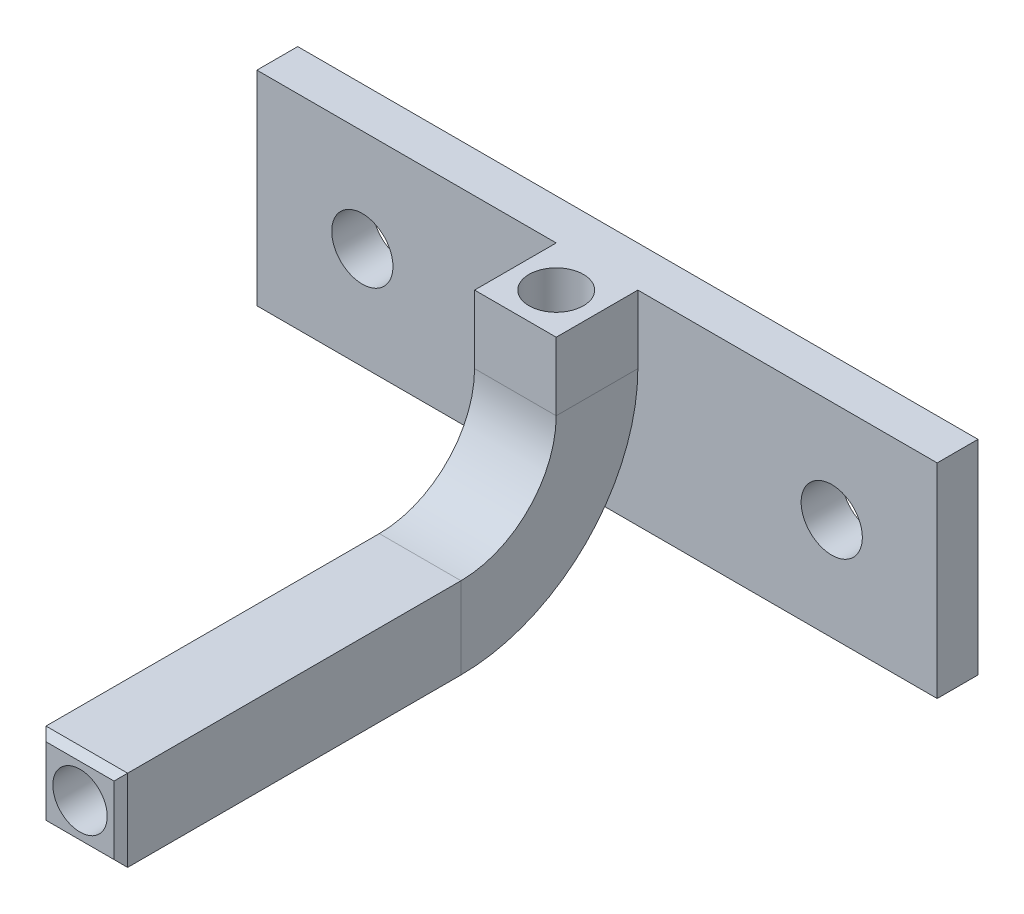
SolidWorks part; units mm, degrees
ref_plane "Спереди" through (0, 0, 0) normal (0, 0, 1) x (1, 0, 0)
ref_plane "Сверху" through (0, 0, 0) normal (0, 1, 0) x (1, 0, 0)
ref_plane "Справа" through (0, 0, 0) normal (1, 0, 0) x (0, 0, -1)
sketch "Эскиз1" plane through (0, 0, 0) normal (0, 0, 1) x (1, 0, 0)
  line L0 (-17.25, 0) -> (17.25, 0) construction
  line L1 (-25, -7.5) -> (25, -7.5)
  line L2 (-25, -7.5) -> (-25, 7.5)
  line L3 (-25, 7.5) -> (25, 7.5)
  line L4 (25, -7.5) -> (25, 7.5)
  line L5 (-25, -7.5) -> (25, 7.5) construction
  line L6 (-25, 7.5) -> (25, -7.5) construction
  circle A0 centre (17.25, 0) radius 2.25
  circle A1 centre (-17.25, 0) radius 2.25
  point P0 (0, 0)
  dimension "D3" = 4.5
  dimension "D4" = 4.5
  dimension "D1" = 50
  dimension "D2" = 34.5
  dimension "D5" = 15
extrude "Бобышка-Вытянуть1" add sketch "Эскиз1" along normal blind 3
sketch "Эскиз4" plane through (0, 7.5, 0) normal (0, 1, 0) x (1, 0, 0)
  line L0 (25, -3) -> (-25, -3) construction
  line L1 (3, -9) -> (-3, -9)
  line L2 (3, -9) -> (3, -3)
  line L3 (3, -3) -> (-3, -3)
  line L4 (-3, -9) -> (-3, -3)
  line L5 (3, -9) -> (-3, -3) construction
  line L6 (3, -3) -> (-3, -9) construction
  line L7 (0, 0) -> (0, -6) construction
  line L9 (25, 0) -> (-25, 0) construction
  circle A0 centre (0, -6) radius 2
  point P0 (0, -6)
  dimension "D3" = 4
  dimension "D1" = 6
  dimension "D2" = 6
ref_plane "Плоскость4" through (0, 0, 0) normal (-1, 0, 0) x (0, 0, 1)
sketch "Эскиз5" plane through (0, 0, 0) normal (-1, 0, 0) x (0, 0, 1)
  line L0 (6, 7.5) -> (6, 2.5)
  line L1 (16, -7.5) -> (41, -7.5)
  arc A0 (6, 2.5) -> (16, -7.5) centre (16, 2.5) ccw
  point P6 (6, -7.5)
  dimension "D3" = 10
  dimension "D1" = 15
  dimension "D2" = 35
sweep "По траектории1" add profiles "Эскиз4" path "Эскиз5"
chamfer "Фаска1" distance 0.5 angle 45 4 edges at (3, -7.5, 41) (0, -10.5, 41) (-3, -7.5, 41) (0, -4.5, 41)
